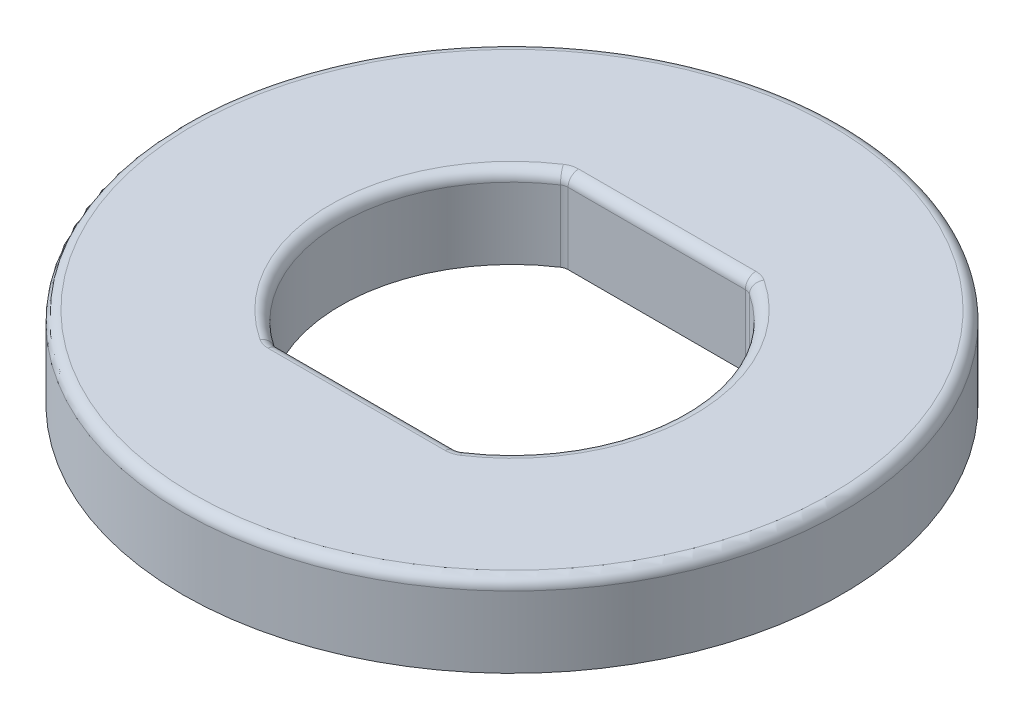
SolidWorks part; units mm, degrees
material "Plain Carbon Steel"
ref_plane "Front Plane" through (0, 0, 0) normal (0, 0, 1) x (1, 0, 0)
ref_plane "Top Plane" through (0, 0, 0) normal (0, 1, 0) x (1, 0, 0)
ref_plane "Right Plane" through (0, 0, 0) normal (1, 0, 0) x (0, 0, -1)
sketch "Sketch1" plane through (0, 0, 0) normal (0, 1, 0) x (1, 0, 0)
  line L0 (3.3023, 5.207) -> (-3.3023, 5.207)
  line L1 (-3.3023, -5.207) -> (3.3023, -5.207)
  line L2 (0, 0) -> (-13203.3812, 0) construction
  circle A0 centre (0, 0) radius 11.8618
  arc A1 (-3.3023, 5.207) -> (-3.3023, -5.207) centre (0, 0) ccw
  arc A2 (3.3023, 5.207) -> (-3.3023, 5.207) centre (0, 0) ccw construction
  arc A3 (-3.3023, -5.207) -> (3.3023, -5.207) centre (0, 0) ccw construction
  arc A4 (3.3023, -5.207) -> (3.3023, 5.207) centre (0, 0) ccw
  dimension "D2" = 12.3317
  dimension "D3" = 23.7236
  dimension "D1" = 10.414
extrude "Boss-Extrude1" add sketch "Sketch1" along normal mid plane 2.9464 contours A0 L2 A1
fillet "Fillet1" radius 0.381 9 edges at (0, 1.4732, 11.8618) (0, 1.4732, -5.207) (-6.1658, 1.4732, 0) (0, 1.4732, 5.207) (6.1658, 1.4732, 0) (3.3023, 0, -5.207) (-3.3023, 0, 5.207) (3.3023, 0, 5.207) (-3.3023, 0, -5.207)
